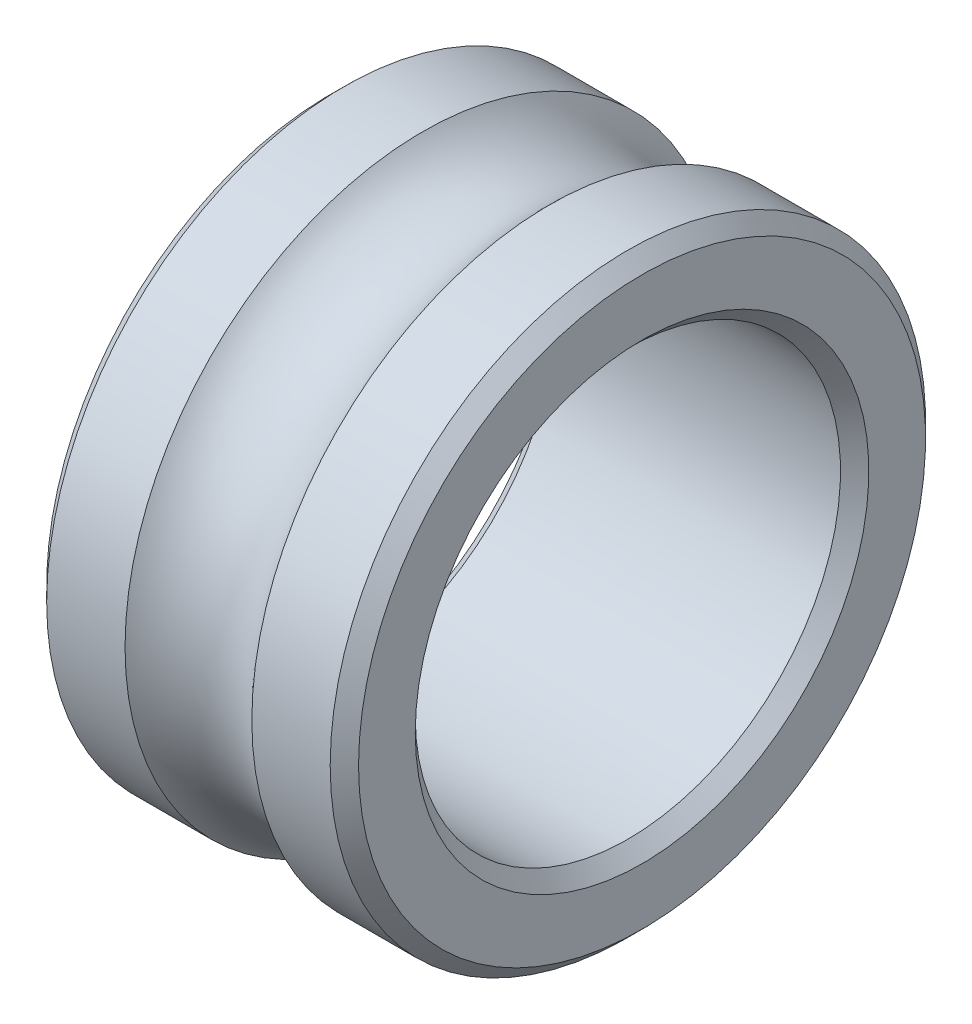
SolidWorks part; units mm, degrees
ref_plane "Front Plane" through (0, 0, 0) normal (0, 0, 1) x (1, 0, 0)
ref_plane "Top Plane" through (0, 0, 0) normal (0, 1, 0) x (1, 0, 0)
ref_plane "Right Plane" through (0, 0, 0) normal (1, 0, 0) x (0, 0, -1)
sketch "Sketch1" plane through (0, 0, 0) normal (0, 0, 1) x (1, 0, 0)
  line L0 (-28.2911, 0) -> (21.8354, 0) construction
  line L1 (0, 7.5) -> (0, 0) construction
  line L2 (5.5, 10.5) -> (2.2361, 10.5)
  line L3 (5.5, 10.5) -> (5.5, 7.5)
  line L4 (5.5, 7.5) -> (-5.5, 7.5)
  line L5 (-5.5, 10.5) -> (-5.5, 7.5)
  line L6 (5.5, 10.5) -> (-5.5, 7.5) construction
  line L7 (5.5, 7.5) -> (-5.5, 10.5) construction
  line L8 (-2.2361, 10.5) -> (-5.5, 10.5)
  arc A0 (-2.2361, 10.5) -> (2.2361, 10.5) centre (0, 12.5) ccw
  point P3 (0, 9)
  point P11 (0, 7.5)
  point P14 (0, 0)
  point P15 (0, 0)
  point P16 (0, 0)
  point P17 (0, 9.5)
  dimension "D4" = 2
  dimension "D5" = 3
  dimension "D1" = 11
  dimension "D2" = 7.5
  dimension "D3" = 10.5
  dimension "D6" = 1
  dimension "D7" = 3
revolve "Revolve1" add sketch "Sketch1" angle 360 about L0
chamfer "Chamfer1" distance 0.5 angle 45 4 edges at (5.5, 0, 10.5) (5.5, 0, 7.5) (-5.5, 0, 10.5) (-5.5, 0, 7.5)
